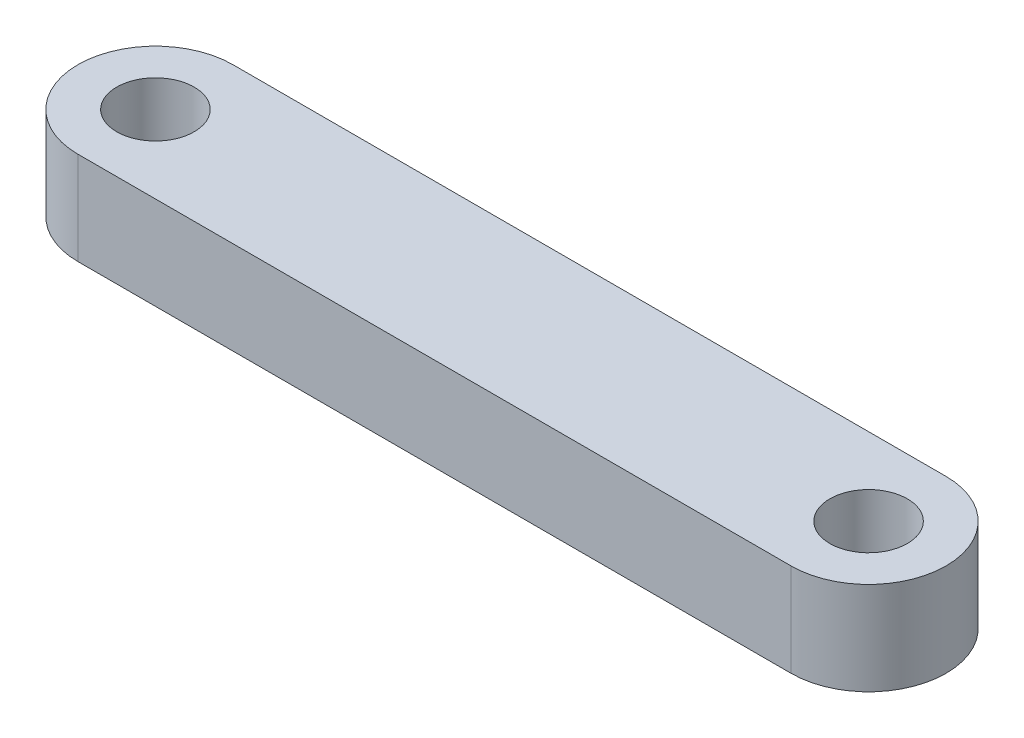
SolidWorks part; units mm, degrees
ref_plane "Front Plane" through (0, 0, 0) normal (0, 0, 1) x (1, 0, 0)
ref_plane "Top Plane" through (0, 0, 0) normal (0, 1, 0) x (1, 0, 0)
ref_plane "Right Plane" through (0, 0, 0) normal (1, 0, 0) x (0, 0, -1)
sketch "Sketch1" plane through (0, 0, 0) normal (0, 1, 0) x (1, 0, 0)
  line L0 (11.5, 0) -> (-11.5, 0) construction
  line L1 (11.5, -2.5) -> (-11.5, -2.5)
  line L2 (11.5, 2.5) -> (-11.5, 2.5)
  arc A0 (11.5, -2.5) -> (11.5, 2.5) centre (11.5, 0) ccw
  arc A1 (-11.5, 2.5) -> (-11.5, -2.5) centre (-11.5, 0) ccw
  point P2 (0, 0)
  dimension "D1" = 23
  dimension "D2" = 5
extrude "Boss-Extrude1" add sketch "Sketch1" along normal blind 3
sketch "Sketch2" plane through (0, 3, 0) normal (0, 1, 0) x (1, 0, 0)
  circle A0 centre (11.5, 0) radius 1.25
  circle A1 centre (-11.5, 0) radius 1.25
  dimension "D1" = 2.5
  dimension "D2" = 2.5
extrude "Cut-Extrude1" cut sketch "Sketch2" against normal through all
